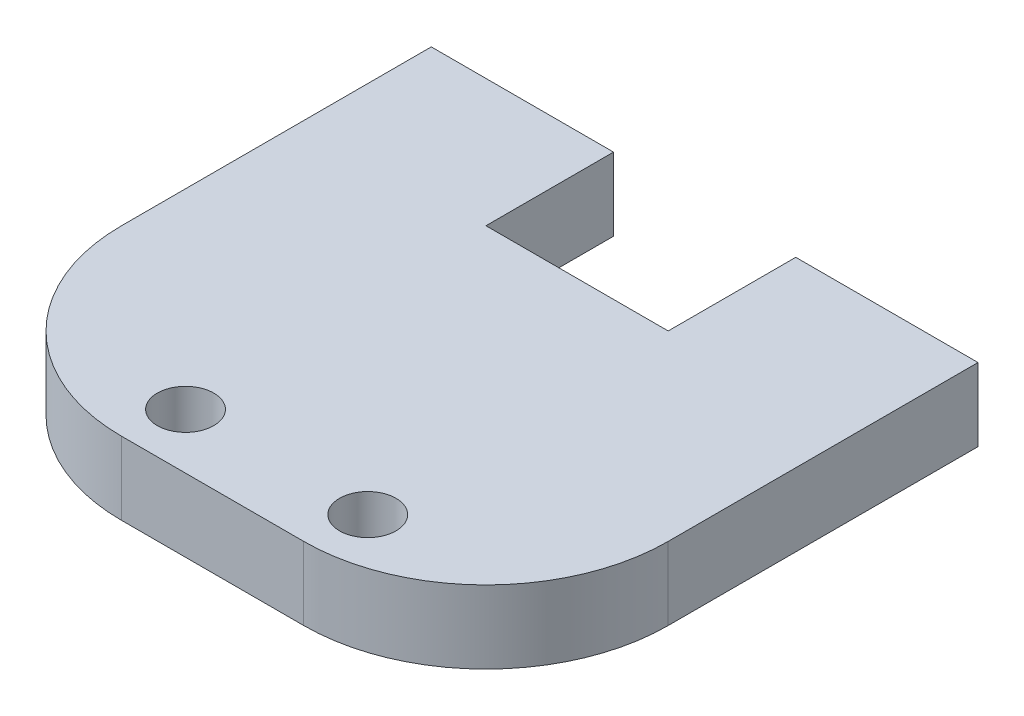
SolidWorks part; units mm, degrees
ref_plane "Plan de face" through (0, 0, 0) normal (0, 0, 1) x (1, 0, 0)
ref_plane "Plan de dessus" through (0, 0, 0) normal (0, 1, 0) x (1, 0, 0)
ref_plane "Plan de droite" through (0, 0, 0) normal (1, 0, 0) x (0, 0, -1)
sketch "Esquisse2" plane through (0, 0, 0) normal (0, 1, 0) x (1, 0, 0)
  line L0 (-15, 4.1258) -> (-15, 7)
  line L1 (-15, 7) -> (-5, 7)
  line L2 (-5, 7) -> (-5, 0)
  line L3 (-5, 0) -> (5, 0)
  line L4 (5, 0) -> (5, 7)
  line L5 (5, 7) -> (15, 7)
  line L6 (15, 7) -> (15, 0.9995)
  line L7 (-15, 4.1258) -> (-15, -20)
  line L8 (-15, -20) -> (15, -20)
  line L9 (15, -20) -> (15, 0.9995)
  line L10 (-1.5, -21) -> (-7.85, -21) construction
  point P2 (0, 0)
  dimension "D1" = 30
  dimension "D2" = 10
  dimension "D3" = 7
  dimension "D4" = 7
  dimension "D5" = 1
extrude "Boss.-Extru.1" add sketch "Esquisse2" along normal blind 4
fillet "Congé1" radius 10 2 edges at (-15, 2, 20) (15, 2, 20)
sketch "Esquisse3" plane through (0, 4, 0) normal (0, 1, 0) x (1, 0, 0)
  circle A0 centre (5.4835, -16.9691) radius 1.55 construction
  circle A1 centre (-4.5165, -16.9691) radius 1.55 construction
  circle A2 centre (5.4835, -16.9691) radius 1.55
  circle A3 centre (-4.5165, -16.9691) radius 1.55
extrude "Enlèv. mat.-Extru.1" cut sketch "Esquisse3" against normal blind 10
